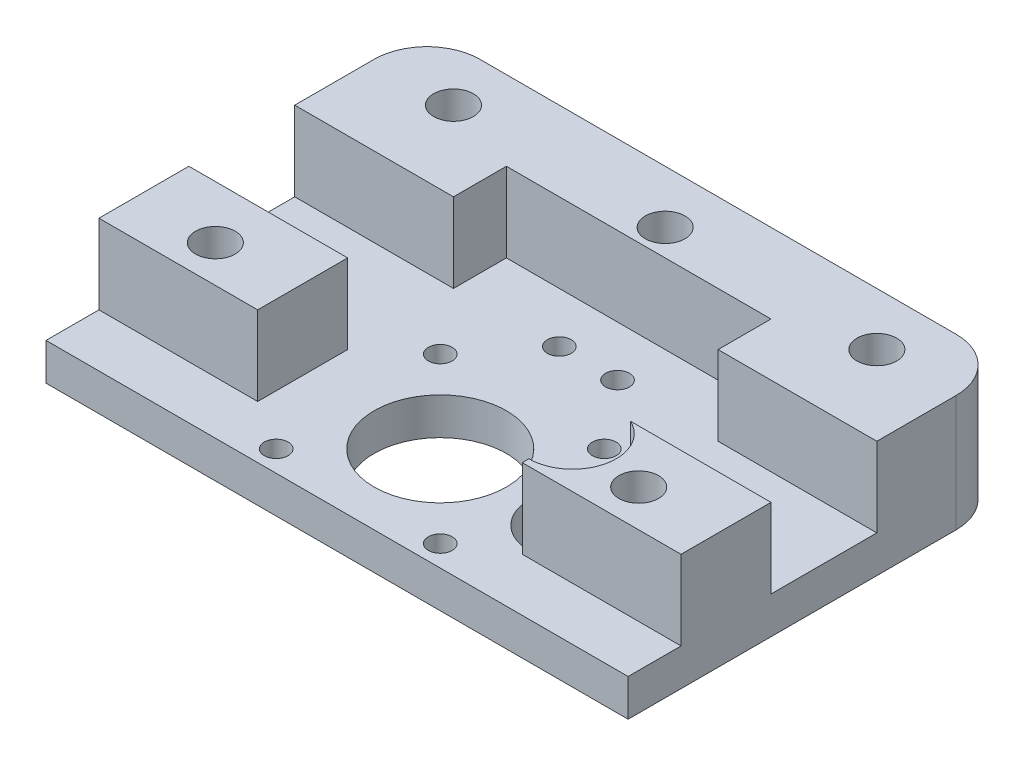
SolidWorks part; units mm, degrees
ref_plane "Front Plane" through (0, 0, 0) normal (0, 0, 1) x (1, 0, 0)
ref_plane "Top Plane" through (0, 0, 0) normal (0, 1, 0) x (1, 0, 0)
ref_plane "Right Plane" through (0, 0, 0) normal (1, 0, 0) x (0, 0, -1)
sketch "Sketch1" plane through (0, 0, 0) normal (0, 1, 0) x (1, 0, 0)
  line L0 (0, 0) -> (0, 36) construction
  line L1 (-55, 36) -> (55, 36)
  line L2 (-55, 36) -> (-55, -36)
  line L3 (-55, -36) -> (55, -36)
  line L4 (55, 36) -> (55, -36)
  line L5 (-55, 36) -> (55, -36) construction
  line L6 (-55, -36) -> (55, 36) construction
  line L15 (-15.5, -32) -> (15.5, -32) construction
  line L16 (-15.5, -32) -> (-15.5, -1) construction
  line L17 (-15.5, -1) -> (15.5, -1) construction
  line L18 (15.5, -32) -> (15.5, -1) construction
  line L19 (-15.5, -32) -> (15.5, -1) construction
  line L20 (-15.5, -1) -> (15.5, -32) construction
  circle A8 centre (0, -16.5) radius 12.5
  circle A9 centre (-15.5, -32) radius 2.25
  circle A10 centre (-15.5, -1) radius 2.25
  circle A11 centre (15.5, -1) radius 2.25
  circle A12 centre (15.5, -32) radius 2.25
  circle A13 centre (25, -16.5) radius 8.25
  circle A19 centre (-5.5, 11.5) radius 2.25
  circle A20 centre (5.5, 11.5) radius 2.25
  point P0 (0, 0)
  dimension "D2" = 25
  dimension "D4" = 16.5
  dimension "D5" = 4.5
  dimension "D6" = 16.5
  dimension "D7" = 25
  dimension "D15" = 4.5
  dimension "D1" = 110
  dimension "D3" = 31
  dimension "D8" = 72
  dimension "D14" = 24.5
  dimension "D16" = 5.5
  dimension "D17" = 11
extrude "Boss-Extrude1" add sketch "Sketch1" along normal blind 7
sketch "Sketch2" plane through (0, 7, 0) normal (0, 1, 0) x (1, 0, 0)
  line L1 (-55, 36) -> (55, 36)
  line L2 (-55, 36) -> (-55, -26)
  line L3 (-55, -26) -> (-25, -26)
  line L4 (-25, 21) -> (-25, -26)
  line L5 (-55, -36) -> (55, -36) construction
  line L6 (25, 21) -> (-25, 21)
  line L8 (55, 36) -> (55, -26)
  line L9 (55, -26) -> (25, -26)
  line L10 (25, 21) -> (25, -26)
  dimension "D1" = 30
  dimension "D4" = 15
  dimension "D5" = 10
extrude "Boss-Extrude2" add sketch "Sketch2" along normal blind 15
fillet "Fillet2" radius 10 2 edges at (55, 11, -36) (-55, 11, -36)
sketch "Sketch3" plane through (0, 0, 0) normal (0, -1, 0) x (1, 0, 0)
  line L0 (45, -36) -> (-45, -36) construction
  line L1 (55, 36) -> (55, -26) construction
  line L2 (-55, -26) -> (-55, 36) construction
  circle A0 centre (40, -26) radius 3.75
  circle A1 centre (-40, -26) radius 3.75
  circle A2 centre (-40, 19) radius 3.75
  circle A3 centre (0, -26) radius 3.75
  circle A4 centre (40, 19) radius 3.75
  dimension "D1" = 7.5
  dimension "D2" = 10
  dimension "D3" = 15
  dimension "D5" = 15
  dimension "D6" = 45
extrude "Cut-Extrude1" cut sketch "Sketch3" against normal through all
sketch "Sketch4" plane through (0, 22, 0) normal (0, 1, 0) x (1, 0, 0)
  line L0 (55, -26) -> (55, 26) construction
  line L1 (55, -9) -> (25, -9)
  line L2 (55, -9) -> (55, 11)
  line L3 (55, 11) -> (25, 11)
  line L4 (25, -9) -> (25, 11)
  line L5 (25, 21) -> (25, -26) construction
  line L6 (-25, -26) -> (-25, 21) construction
  line L7 (-25, -9) -> (-55, -9)
  line L8 (-25, -9) -> (-25, 11)
  line L9 (-25, 11) -> (-55, 11)
  line L10 (-55, -9) -> (-55, 11)
  line L11 (-55, 26) -> (-55, -26) construction
  line L12 (25, -26) -> (55, -26) construction
  dimension "D1" = 20
  dimension "D2" = 17
extrude "Cut-Extrude2" cut sketch "Sketch4" against normal up to surface (15 mm away) up to face at (4.175, 7, 16.7)
sketch "Sketch5" plane through (0, 7, 0) normal (0, -1, 0) x (1, 0, 0)
  line L2 (25, 24.75) -> (25, 9)
  line L3 (25, 9) -> (28.4369, 9)
  line L4 (25, 24.75) -> (25, 9)
  line L5 (25, 9) -> (28.4369, 9)
  arc A1 (28.4369, 9) -> (25, 24.75) centre (25, 16.5) ccw
  arc A2 (28.4369, 9) -> (25, 24.75) centre (25, 16.5) ccw
  dimension "D1" = 0
extrude "Cut-Extrude3" cut sketch "Sketch5" against normal through all
